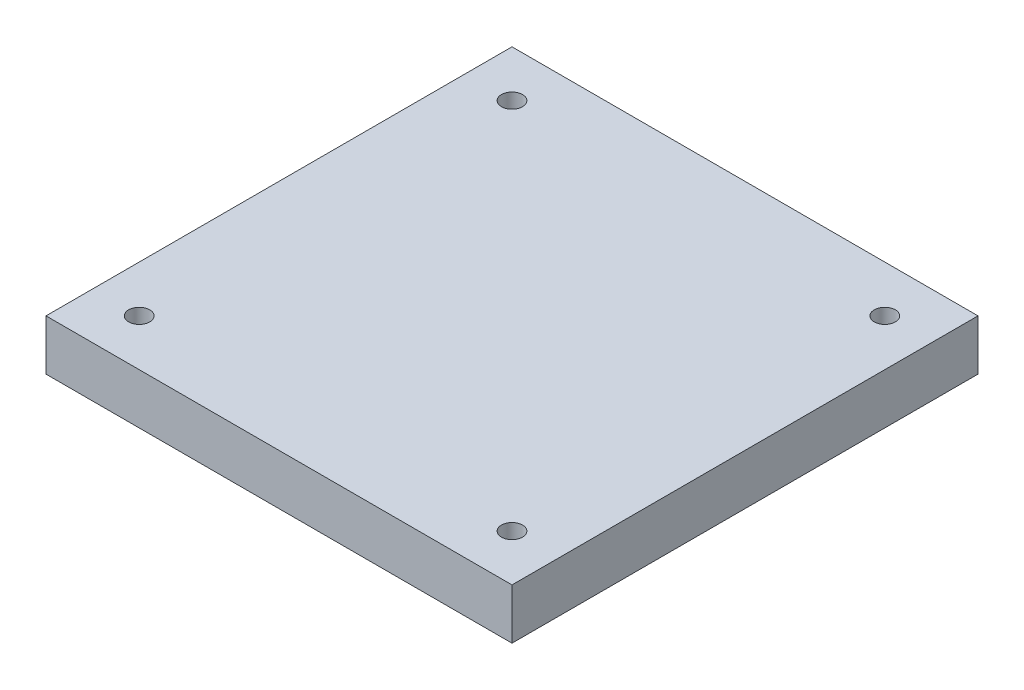
SolidWorks part; units mm, degrees
ref_plane "Front Plane" through (0, 0, 0) normal (0, 0, 1) x (1, 0, 0)
ref_plane "Top Plane" through (0, 0, 0) normal (0, 1, 0) x (1, 0, 0)
ref_plane "Right Plane" through (0, 0, 0) normal (1, 0, 0) x (0, 0, -1)
sketch "Sketch1" plane through (0, 0, 0) normal (0, 0, 1) x (1, 0, 0)
  line L7 (-50.8, -5.5562) -> (50.8, -5.5562)
  line L8 (-50.8, -5.5562) -> (-50.8, 5.5562)
  line L9 (-50.8, 5.5562) -> (50.8, 5.5562)
  line L10 (50.8, -5.5562) -> (50.8, 5.5562)
  line L11 (-50.8, -5.5562) -> (50.8, 5.5562) construction
  line L12 (-50.8, 5.5562) -> (50.8, -5.5562) construction
  point P4 (0, 0)
  point P14 (0, 0)
  dimension "Width" = 101.6
  dimension "Thickness" = 11.1125
sketch "Sketch2" plane through (0, 0, 0) normal (0, 1, 0) x (0, 0, -1)
  line L0 (50.8, 50.8) -> (-50.8, 50.8) construction
  point P0 (76.2, 50.8)
  point P4 (0, 50.8)
  point P6 (-76.2, 50.8)
  dimension "Length" = 101.6
  dimension "D1" = 127
  dimension "D2" = 127
sketch "Sketch3" plane through (0, 0, 0) normal (0, 0, 1) x (1, 0, 0)
  line L6 (-50.8, 5.5562) -> (50.8, 5.5562)
  line L7 (50.8, 5.5562) -> (50.8, -5.5562)
  line L8 (50.8, -5.5562) -> (-50.8, -5.5562)
  line L9 (-50.8, -5.5562) -> (-50.8, 5.5562)
extrude "Boss-Extrude1" add sketch "Sketch3" along normal mid plane 101.6
ref_plane "FacingTop" through (0, 5.1594, 0) normal (0, 1, 0) x (1, 0, 0)
other "FacingTopSurfaceCut"
ref_plane "FacingBottom" through (0, -5.1594, 0) normal (0, -1, 0) x (-1, 0, 0)
other "FacingBottomSurfaceCut"
sketch "BaseBorderRadiusSketch" plane through (0, 5.1594, 0) normal (0, 1, 0) x (1, 0, 0)
  line L0 (50.8, -50.8) -> (50.8, 50.8) construction
  line L1 (-47.625, -47.625) -> (47.625, -47.625)
  line L2 (-47.625, -47.625) -> (-47.625, 47.625)
  line L3 (-47.625, 47.625) -> (47.625, 47.625)
  line L4 (47.625, -47.625) -> (47.625, 47.625)
  line L5 (-47.625, -47.625) -> (47.625, 47.625) construction
  line L6 (-47.625, 47.625) -> (47.625, -47.625) construction
  point P0 (0, 0)
  dimension "D1" = 3.175
extrude "BaseBorderRadiusCut-Extrude" cut sketch "BaseBorderRadiusSketch" against normal through all flip side to cut
sketch "BumperInsetSketch" plane through (0, -5.1594, 0) normal (0, -1, 0) x (1, 0, 0)
  line L1 (-38.1, -38.1) -> (38.1, -38.1) construction
  line L2 (-38.1, -38.1) -> (-38.1, 38.1) construction
  line L3 (-38.1, 38.1) -> (38.1, 38.1) construction
  line L4 (38.1, -38.1) -> (38.1, 38.1) construction
  line L5 (-38.1, -38.1) -> (38.1, 38.1) construction
  line L6 (-38.1, 38.1) -> (38.1, -38.1) construction
  line L7 (47.625, 47.625) -> (47.625, -47.625) construction
  circle A0 centre (-38.1, 38.1) radius 5.715
  circle A1 centre (38.1, 38.1) radius 5.715
  circle A2 centre (38.1, -38.1) radius 5.715
  circle A3 centre (-38.1, -38.1) radius 5.715
  point P0 (0, 0)
  dimension "D2" = 11.43
  dimension "D1" = 9.525
hole_wizard "Bumper#6-32 Tapped Hole" positions "3DSketch4" profile "Sketch11" counterbore size "#6" standard "ANSI Inch" end condition through all
sketch3d "3DSketch4"
  point P0 (-38.1, -5.1594, 38.1)
sketch "Sketch11" plane through (-38.1, -5.1594, 38.1) normal (1, 0, 0) x (0, 0, -1)
  line L0 (0, 0) -> (0, 10.3187)
  line L1 (0, 10.3187) -> (2.1526, 10.3187)
  line L3 (2.1526, 10.3187) -> (2.1526, 5.3848)
  line L4 (2.1526, 5.3848) -> (3.9688, 5.3848)
  line L5 (3.9688, 5.3848) -> (3.9688, 0)
  line L7 (3.9688, 0) -> (0, 0)
  line L11 (0, -6.35) -> (0, 107.95) construction
  dimension "Thru Hole Dia." = 4.3053
  dimension "Thru Hole Depth" = 10.3187
  dimension "C'Bore Dia." = 7.9375
  dimension "C'Bore Depth" = 5.3848
pattern_linear "BumperThreadLPattern" count 2 spacing 76.2 along (0, 0, -1) count 2 spacing 76.2 along (1, 0, 0) of "Bumper#6-32 Tapped Hole"
equation "\"D1@Boss-Extrude1\" = \"Length@Sketch2\""
equation "\"D1@Sketch2\"=\"Width@Sketch1\" * 1.25"
equation "\"D2@Sketch2\"=\"D1@Sketch2\""
